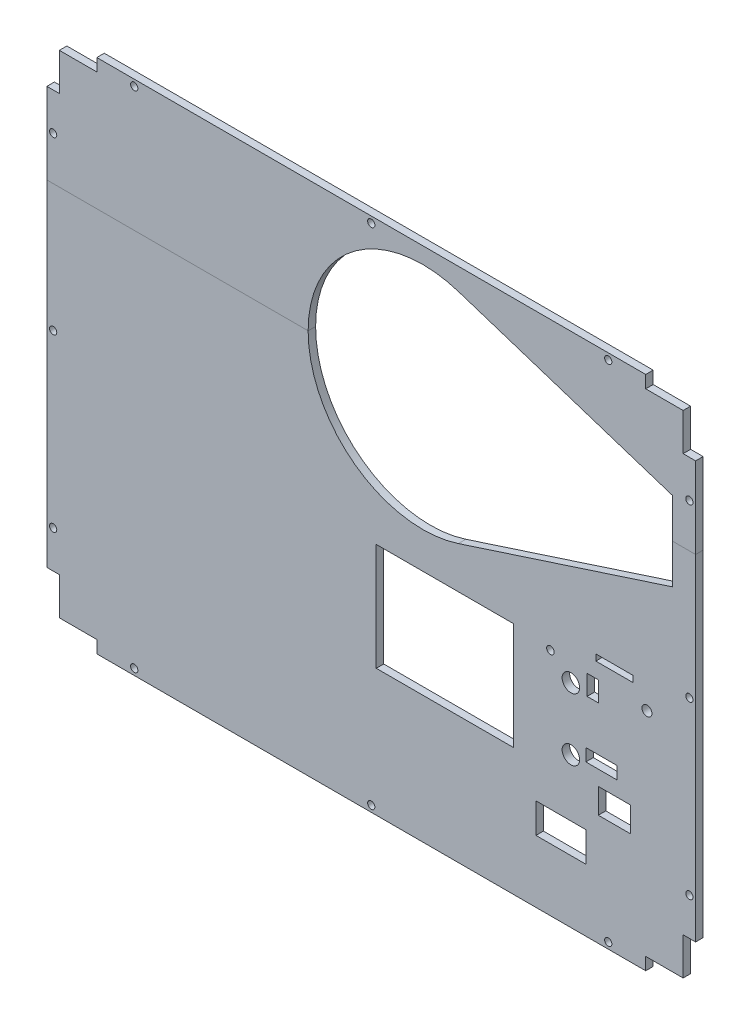
SolidWorks part; units mm, degrees
ref_plane "Front Plane" through (0, 0, 0) normal (0, 0, 1) x (1, 0, 0)
ref_plane "Top Plane" through (0, 0, 0) normal (0, 1, 0) x (1, 0, 0)
ref_plane "Right Plane" through (0, 0, 0) normal (1, 0, 0) x (0, 0, -1)
sketch "Sketch1" plane through (0, 0, 0) normal (0, 0, 1) x (1, 0, 0)
  line L1 (-130, 202) -> (130, 202)
  line L2 (-130, 202) -> (-130, -5)
  line L3 (-130, -5) -> (130, -5)
  line L4 (130, 202) -> (130, -5)
  line L5 (-130, 202) -> (-110, 202)
  line L6 (-130, 202) -> (-130, 197)
  line L7 (-130, 197) -> (-110, 197)
  line L8 (-110, 202) -> (-110, 197)
  line L10 (-130, 202) -> (-125, 202)
  line L11 (-130, 202) -> (-130, 182)
  line L12 (-130, 182) -> (-125, 182)
  line L13 (-125, 202) -> (-125, 182)
  line L15 (-130, -5) -> (-110, -5)
  line L16 (-130, -5) -> (-130, 0)
  line L17 (-130, 0) -> (-110, 0)
  line L18 (-110, -5) -> (-110, 0)
  line L20 (-130, -5) -> (-125, -5)
  line L21 (-130, -5) -> (-130, 15)
  line L22 (-130, 15) -> (-125, 15)
  line L23 (-125, -5) -> (-125, 15)
  line L24 (130, -5) -> (125, -5)
  line L25 (130, -5) -> (130, 15)
  line L26 (130, 15) -> (125, 15)
  line L27 (125, -5) -> (125, 15)
  line L29 (130, -5) -> (110, -5)
  line L30 (130, -5) -> (130, 0)
  line L31 (130, 0) -> (110, 0)
  line L32 (110, -5) -> (110, 0)
  line L33 (130, 202) -> (125, 202)
  line L34 (130, 202) -> (130, 182)
  line L35 (130, 182) -> (125, 182)
  line L36 (125, 202) -> (125, 182)
  line L37 (130, 202) -> (110, 202)
  line L38 (130, 202) -> (130, 197)
  line L39 (130, 197) -> (110, 197)
  line L40 (110, 202) -> (110, 197)
  dimension "D1" = 20
extrude "Boss-Extrude1" add sketch "Sketch1" along normal blind 3 contours L40 L1 L8 L7 L13 L12 L2 L22 L23 L17 L18 L3 L32 L31 L27 L26 L4 L35 L36 L39
sketch "Sketch2" plane through (0, 0, 3) normal (0, 0, 1) x (1, 0, 0)
  line L1 (34.9148, 105.7514) -> (120.7, 133.6247)
  line L2 (120.7, 133.6247) -> (120.7, 165.3753)
  line L3 (120.7, 165.3753) -> (34.9148, 193.2486)
  line L4 (118.7, 163.9222) -> (34.2967, 191.3465)
  line L5 (34.2967, 107.6535) -> (118.7, 135.0778)
  line L6 (118.7, 135.0778) -> (118.7, 163.9222)
  line L7 (118.7, 163.9222) -> (34.2967, 191.3465) construction
  line L8 (34.2967, 107.6535) -> (118.7, 135.0778) construction
  line L9 (118.7, 135.0778) -> (118.7, 163.9222) construction
  arc A0 (34.9148, 193.2486) -> (34.9148, 105.7514) centre (20.7, 149.5) ccw
  arc A1 (34.2967, 191.3465) -> (34.2967, 107.6535) centre (20.7, 149.5) ccw
  arc A2 (34.2967, 191.3465) -> (34.2967, 107.6535) centre (20.7, 149.5) ccw construction
  dimension "D1" = 0
  dimension "D2" = 2
extrude "Cut-Extrude1" cut sketch "Sketch2" against normal through all
sketch "Sketch3" plane through (0, 0, 3) normal (0, 0, 1) x (1, 0, 0)
  line L0 (-110, -5) -> (110, -5) construction
  line L1 (57, 89) -> (2, 89)
  line L2 (57, 89) -> (57, 46)
  line L3 (57, 46) -> (2, 46)
  line L4 (2, 89) -> (2, 46)
  line L5 (130, 182) -> (130, 15) construction
  dimension "D1" = 94
  dimension "D2" = 73
  dimension "D3" = 43
  dimension "D4" = 55
extrude "Cut-Extrude2" cut sketch "Sketch3" against normal through all
sketch "Sketch4" plane through (0, 0, 3) normal (0, 0, 1) x (1, 0, 0)
  line L0 (-130, 149.5) -> (130, 149.5)
  line L1 (-130, 182) -> (-130, 15) construction
  line L2 (130, 182) -> (130, 15) construction
  arc A0 (34.9148, 193.2486) -> (34.9148, 105.7514) centre (20.7, 149.5) ccw construction
  point P9 (-25.3, 149.5)
split "Split1" trim tools "Sketch4" bodies to split 103 resulting bodies 104 105
sketch "Sketch5" plane through (0, 0, 3) normal (0, 0, 1) x (1, 0, 0)
  line L0 (-110, -5) -> (110, -5) construction
  line L1 (66, 20) -> (86, 20)
  line L2 (66, 20) -> (66, 32)
  line L3 (66, 32) -> (86, 32)
  line L4 (86, 20) -> (86, 32)
  line L5 (130, 149.5) -> (130, 15) construction
  dimension "D1" = 37
  dimension "D2" = 12
  dimension "D3" = 64
  dimension "D4" = 20
extrude "Cut-Extrude3" cut sketch "Sketch5" against normal through all
sketch "Sketch6" plane through (0, 0, 3) normal (0, 0, 1) x (1, 0, 0)
  line L0 (80, 55) -> (80, 80) construction
  line L1 (130, 149.5) -> (130, 15) construction
  line L3 (57, 67.5) -> (106.4162, 67.5) construction
  line L4 (57, 46) -> (57, 89) construction
  line L5 (80, 67.5) -> (106.497, 67.5) construction
  circle A0 centre (80, 55) radius 3.5
  circle A1 centre (80, 80) radius 3.5
  point P4 (80, 67.5)
  dimension "D1" = 50
  dimension "D2" = 25
  dimension "D3" = 7
  dimension "D4" = 0
extrude "Cut-Extrude4" cut sketch "Sketch6" against normal through all
sketch "Sketch7" plane through (0, 0, 3) normal (0, 0, 1) x (1, 0, 0)
  line L0 (-110, 199.5) -> (110, 199.5) construction
  line L1 (-110, 197) -> (-110, 202) construction
  line L2 (110, 197) -> (110, 202) construction
  line L3 (127.5, 182) -> (127.5, 15) construction
  line L4 (130, 182) -> (125, 182) construction
  line L5 (130, 15) -> (125, 15) construction
  line L6 (0, 202) -> (0, -5) construction
  line L7 (-110, 202) -> (110, 202) construction
  line L8 (-110, -5) -> (110, -5) construction
  line L9 (-130, 182) -> (-130, 15) construction
  line L10 (-130, 98.5) -> (127.5, 98.5) construction
  circle A1 centre (-95, 199.5) radius 1.45
  circle A2 centre (95, 199.5) radius 1.45
  circle A3 centre (0, 199.5) radius 1.45
  circle A4 centre (127.5, 167) radius 1.45
  circle A5 centre (127.5, 98.5) radius 1.45
  circle A6 centre (127.5, 30) radius 1.45
  circle A7 centre (95, -2.5) radius 1.45
  circle A8 centre (0, -2.5) radius 1.45
  circle A9 centre (-95, -2.5) radius 1.45
  circle A10 centre (-127.5, 30) radius 1.45
  circle A11 centre (-127.5, 98.5) radius 1.45
  circle A12 centre (-127.5, 167) radius 1.45
  dimension "D1" = 2.9
  dimension "D2" = 15
  dimension "D3" = 15
  dimension "D4" = 15
  dimension "D5" = 15
extrude "Cut-Extrude5" cut sketch "Sketch7" against normal through all
sketch "Sketch8" plane through (0, 0, 3) normal (0, 0, 1) x (1, 0, 0)
  line L0 (130, 62) -> (130, 76) construction
  line L1 (86, 55.5) -> (98.5, 55.5)
  line L2 (86, 55.5) -> (86, 60.5)
  line L3 (86, 60.5) -> (98.5, 60.5)
  line L4 (98.5, 55.5) -> (98.5, 60.5)
  line L5 (86.5, 78.5) -> (91, 78.5)
  line L6 (86.5, 78.5) -> (86.5, 86.5)
  line L7 (86.5, 86.5) -> (91, 86.5)
  line L8 (91, 78.5) -> (91, 86.5)
  line L9 (90, 92.5) -> (105, 92.5)
  line L10 (90, 92.5) -> (90, 95)
  line L11 (90, 95) -> (105, 95)
  line L12 (105, 92.5) -> (105, 95)
  line L13 (91, 39.5) -> (104, 39.5)
  line L14 (91, 39.5) -> (91, 49.5)
  line L15 (91, 49.5) -> (104, 49.5)
  line L16 (104, 39.5) -> (104, 49.5)
  line L17 (130, 62) -> (130, 76) construction
  line L19 (130, 149.5) -> (130, 15) construction
  circle A0 centre (110.5, 85.5) radius 2
  circle A1 centre (80, 55) radius 3.5 construction
  circle A2 centre (80, 80) radius 3.5 construction
  circle A3 centre (71.8, 87.2) radius 1.5
  point P24 (88.75, 78.5)
  point P25 (130, 69)
  dimension "D1" = 6
  dimension "D16" = 4
  dimension "D20" = 3
  dimension "D21" = 7.2
  dimension "D2" = 12.5
  dimension "D3" = 5
  dimension "D4" = 5.5
  dimension "D5" = 6.5
  dimension "D6" = 4.5
  dimension "D7" = 8
  dimension "D8" = 12.5
  dimension "D9" = 2.5
  dimension "D10" = 15
  dimension "D11" = 5.5
  dimension "D12" = 10
  dimension "D13" = 13
  dimension "D14" = 11
  dimension "D15" = 16.5
  dimension "D17" = 19.5
  dimension "D18" = 1
  dimension "D19" = 18
  dimension "D22" = 8.2
extrude "Cut-Extrude6" cut sketch "Sketch8" against normal through all
